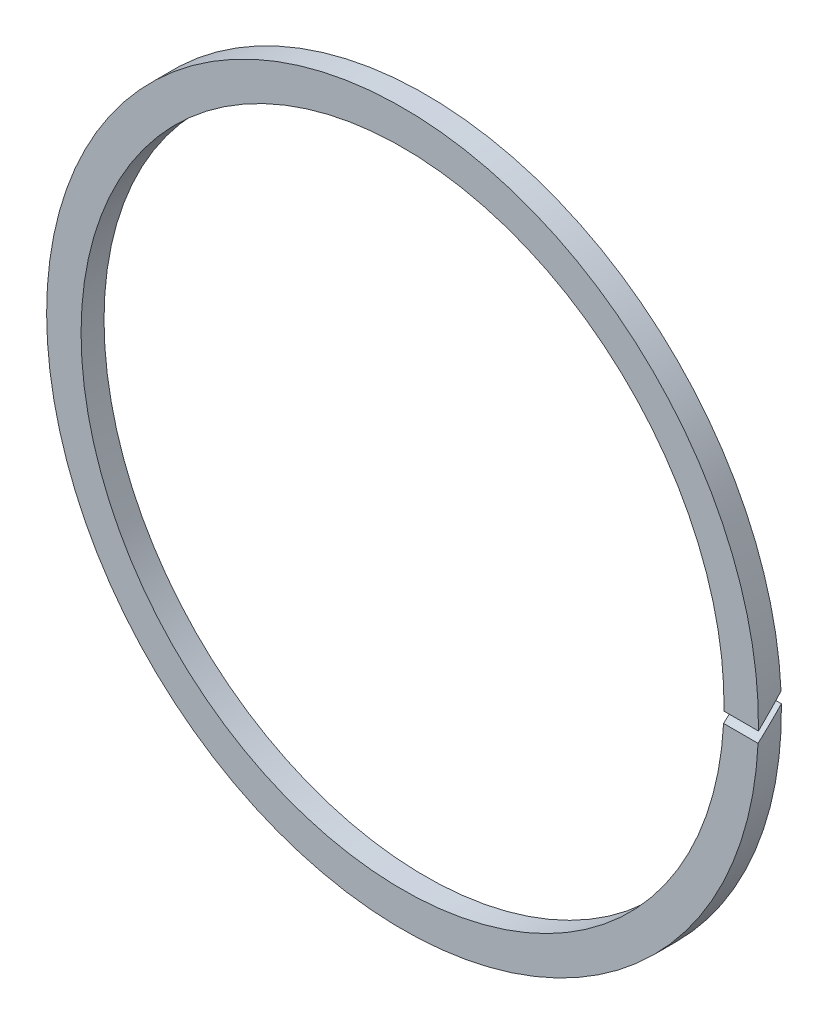
SolidWorks part; units mm, degrees
ref_plane "Front Plane" through (0, 0, 0) normal (0, 0, 1) x (1, 0, 0)
ref_plane "Top Plane" through (0, 0, 0) normal (0, 1, 0) x (1, 0, 0)
ref_plane "Right Plane" through (0, 0, 0) normal (1, 0, 0) x (0, 0, -1)
sketch "Sketch1" plane through (0, 0, 0) normal (0, 0, 1) x (1, 0, 0)
  circle A0 centre (0, 0) radius 46.5
  circle A1 centre (0, 0) radius 42
  dimension "D1" = 93
  dimension "D2" = 84
extrude "Boss-Extrude1" add sketch "Sketch1" along normal blind 3
sketch "Sketch2" plane through (0, 0, 0) normal (1, 0, 0) x (0, 0, -1)
  line L0 (-1.5, 46.5009) -> (-1.5, -46.5) construction
  line L1 (-31.7229, -30.2225) -> (28.7229, 30.2233) construction
  line L2 (-13.2146, -11.7142) -> (-13.5682, -11.3606)
  line L3 (-3, -46.5) -> (0, -46.5) construction
  line L4 (-13.5682, -11.3606) -> (7.0658, 9.2733)
  line L5 (7.0658, 9.2733) -> (7.4194, 8.9198)
  line L6 (7.4194, 8.9198) -> (7.7729, 8.5662)
  line L7 (7.7729, 8.5662) -> (-12.861, -12.0677)
  line L8 (-12.861, -12.0677) -> (-13.2146, -11.7142)
  point P3 (-1.5, 46.5009)
  point P8 (-1.5, 0.0004)
  dimension "D1" = 135
  dimension "D2" = 0.5
  dimension "D3" = 0.5
extrude "Cut-Extrude1" cut sketch "Sketch2" along normal blind 53
